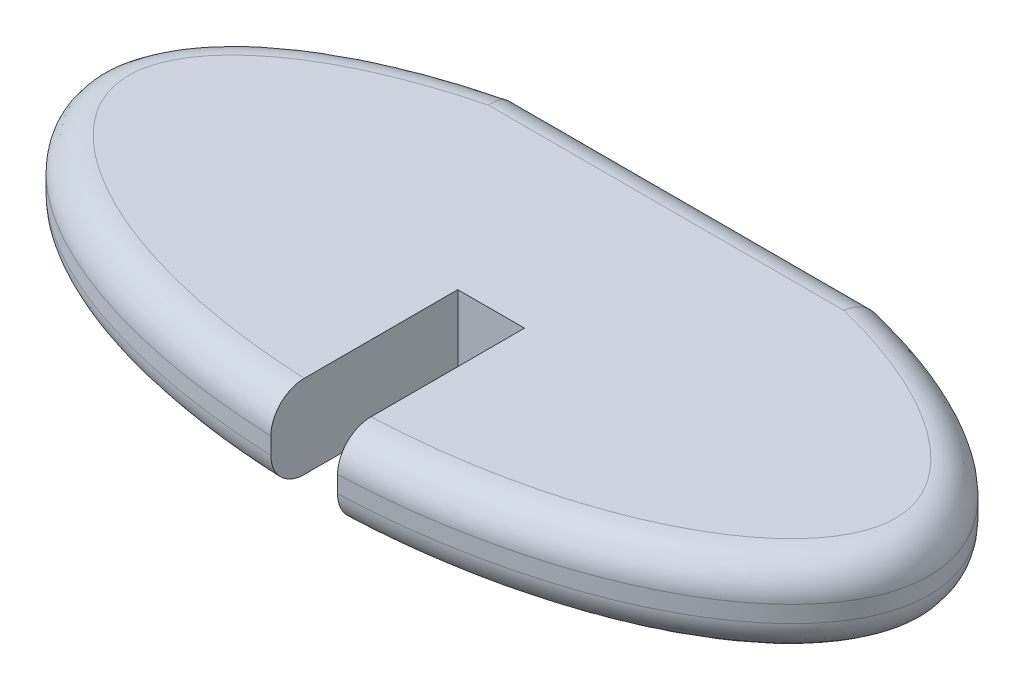
SolidWorks part; units mm, degrees
ref_plane "Front Plane" through (0, 0, 0) normal (0, 0, 1) x (1, 0, 0)
ref_plane "Top Plane" through (0, 0, 0) normal (0, 1, 0) x (1, 0, 0)
ref_plane "Right Plane" through (0, 0, 0) normal (1, 0, 0) x (0, 0, -1)
sketch "Sketch1" plane through (0, 0, 0) normal (0, 1, 0) x (1, 0, 0)
  line L0 (-21.7945, 22.5) -> (21.7945, 22.5)
  ellipse E0 centre (0, 0) end of major axis (50, 0) minor radius 25 (-21.7945, 22.5) -> (21.7945, 22.5) ccw
  dimension "D1" = 50
  dimension "D2" = 25
  dimension "D3" = 22.5
extrude "Boss-Extrude1" add sketch "Sketch1" along normal blind 10
sketch "Sketch5" plane through (0, 10, 0) normal (0, 1, 0) x (1, 0, 0)
  line L0 (-4, -32.5) -> (-4, -2.5)
  line L1 (-4, -32.5) -> (4, -32.5)
  line L2 (-4, -2.5) -> (4, -2.5)
  line L3 (4, -32.5) -> (4, -2.5)
  line L4 (-4, -32.5) -> (4, -2.5) construction
  line L5 (-4, -2.5) -> (4, -32.5) construction
  line L6 (21.7945, 22.5) -> (-21.7945, 22.5) construction
  point P1 (0, -17.5)
  dimension "D1" = 8
  dimension "D2" = 30
  dimension "D3" = 25
  dimension "D4" = 0
extrude "Cut-Extrude4" cut sketch "Sketch5" against normal blind 10
fillet "Fillet12" radius 4 6 edges at (-49.1425, 0, 4.6102) (-49.1425, 10, 4.6102) (49.1425, 0, 4.6102) (49.1425, 10, 4.6102) (0, 0, -22.5) (0, 10, -22.5)
